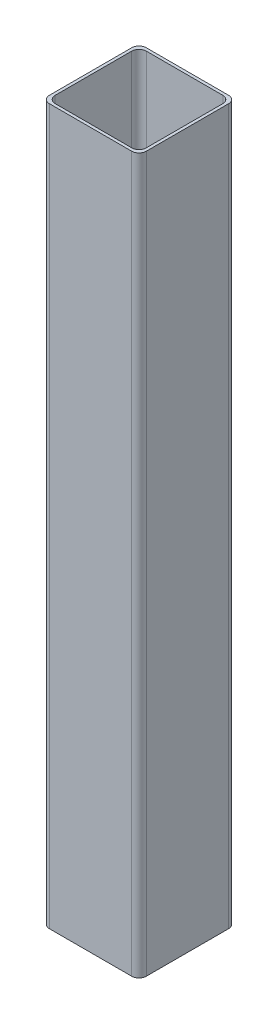
SolidWorks part; units mm, degrees
ref_plane "Plano frontal" through (0, 0, 0) normal (0, 0, 1) x (1, 0, 0)
ref_plane "Plano superior" through (0, 0, 0) normal (0, 1, 0) x (1, 0, 0)
ref_plane "Plano direito" through (0, 0, 0) normal (1, 0, 0) x (0, 0, -1)
sketch "Esboço1" plane through (0, 0, 0) normal (0, 1, 0) x (1, 0, 0)
  line L0 (-18.8, -18.8) -> (-18.8, 18.8)
  line L1 (20, -20) -> (-20, -20)
  line L2 (20, -20) -> (20, 20)
  line L3 (20, 20) -> (-20, 20)
  line L4 (-20, -20) -> (-20, 20)
  line L5 (20, -20) -> (-20, 20) construction
  line L6 (20, 20) -> (-20, -20) construction
  line L7 (18.8, 18.8) -> (-18.8, 18.8)
  line L8 (18.8, -18.8) -> (18.8, 18.8)
  line L9 (18.8, -18.8) -> (-18.8, -18.8)
  point P0 (0, 0)
  dimension "D1" = 40
  dimension "D2" = 40
  dimension "D3" = 1.2
extrude "Ressalto-extrusão1" add sketch "Esboço1" along normal mid plane 295
fillet "Filete1" radius 3 8 edges at (-20, 0, -20) (20, 0, -20) (18.8, 0, -18.8) (18.8, 0, 18.8) (-18.8, 0, 18.8) (-18.8, 0, -18.8) (-20, 0, 20) (20, 0, 20)
